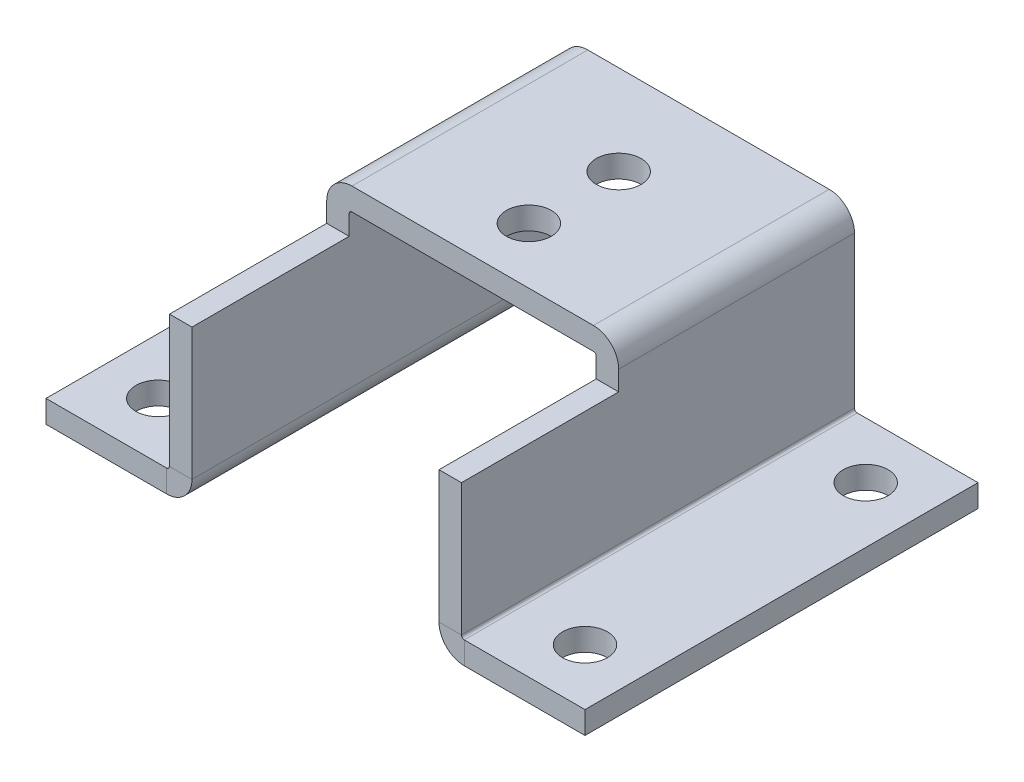
SolidWorks part; units mm, degrees
material "1023 Carbon Steel Sheet (SS)"
ref_plane "Front Plane" through (0, 0, 0) normal (0, 0, 1) x (1, 0, 0)
ref_plane "Top Plane" through (0, 0, 0) normal (0, 1, 0) x (1, 0, 0)
ref_plane "Right Plane" through (0, 0, 0) normal (1, 0, 0) x (0, 0, -1)
sketch "Sketch1" plane through (0, 0, 0) normal (0, 0, 1) x (1, 0, 0)
  line L0 (24, -16) -> (13.25, -16)
  line L1 (12, -14.75) -> (12, -1.25)
  line L2 (10.75, 0) -> (-10.75, 0)
  line L3 (-12, -1.25) -> (-12, -14.75)
  line L4 (-13.25, -16) -> (-24, -16)
  arc A0 (-12, -14.75) -> (-13.25, -16) centre (-13.25, -14.75) cw
  arc A1 (13.25, -16) -> (12, -14.75) centre (13.25, -14.75) cw
  arc A2 (12, -1.25) -> (10.75, 0) centre (10.75, -1.25) ccw
  arc A3 (-10.75, 0) -> (-12, -1.25) centre (-10.75, -1.25) ccw
  point P9 (0, 0)
  point P17 (12, 0)
  point P20 (-12, 0)
  dimension "D4" = 1.25
  dimension "D1" = 48
  dimension "D2" = 16
  dimension "D3" = 24
sketch "Sketch2" plane through (0, 0, 0) normal (1, 0, 0) x (0, 0, -1)
  line L0 (-17.5, 1) -> (17.5, 1)
  line L1 (17.5, 1) -> (17.5, -1)
  line L2 (17.5, -1) -> (-17.5, -1)
  line L3 (-17.5, -1) -> (-17.5, 1)
  point P0 (0, -1)
  point P3 (0, 1)
  dimension "D1" = 1
  dimension "D2" = 1
  dimension "D3" = 35
sweep "Sweep1" add profiles "Sketch2" path "Sketch1"
sketch "Sketch3" plane through (0, 0, 0) normal (1, 0, 0) x (0, 0, -1)
  line L0 (-17.5, 1) -> (-17.5, -3)
  line L1 (-17.5, -1.25) -> (-17.5, -14.75) construction
  line L2 (-17.5, -3) -> (-3.5, -3)
  line L3 (-3.5, -3) -> (-3.5, 1)
  line L4 (17.5, 1) -> (-17.5, 1) construction
  line L5 (-3.5, 1) -> (-17.5, 1)
  dimension "D1" = 14
  dimension "D2" = 4
extrude "Cut-Extrude1" cut sketch "Sketch3" against normal through all both and the other way through all
sketch "Sketch4" plane through (0, 1, 0) normal (0, 1, 0) x (1, 0, 0)
  line L0 (-10.75, 17.5) -> (10.75, 17.5) construction
  line L5 (-24, -17.5) -> (-13.25, -17.5) construction
  line L6 (13.25, -17.5) -> (24, -17.5) construction
  line L7 (0, 0) -> (-19, 0) construction
  line L8 (0, 0) -> (19, 0) construction
  circle A0 centre (0, 1.5) radius 2
  circle A1 centre (0, 9.5) radius 2
  circle A2 centre (-19, 12.5) radius 2
  circle A3 centre (-19, -12.5) radius 2
  circle A4 centre (19, -12.5) radius 2
  circle A5 centre (19, 12.5) radius 2
  dimension "D2" = 4
  dimension "D5" = 5
  dimension "D1" = 8
  dimension "D3" = 16
  dimension "D6" = 25
  dimension "D7" = 5
  dimension "D8" = 25
  dimension "D9" = 38
extrude "Cut-Extrude2" cut sketch "Sketch4" against normal through all both and the other way through all
